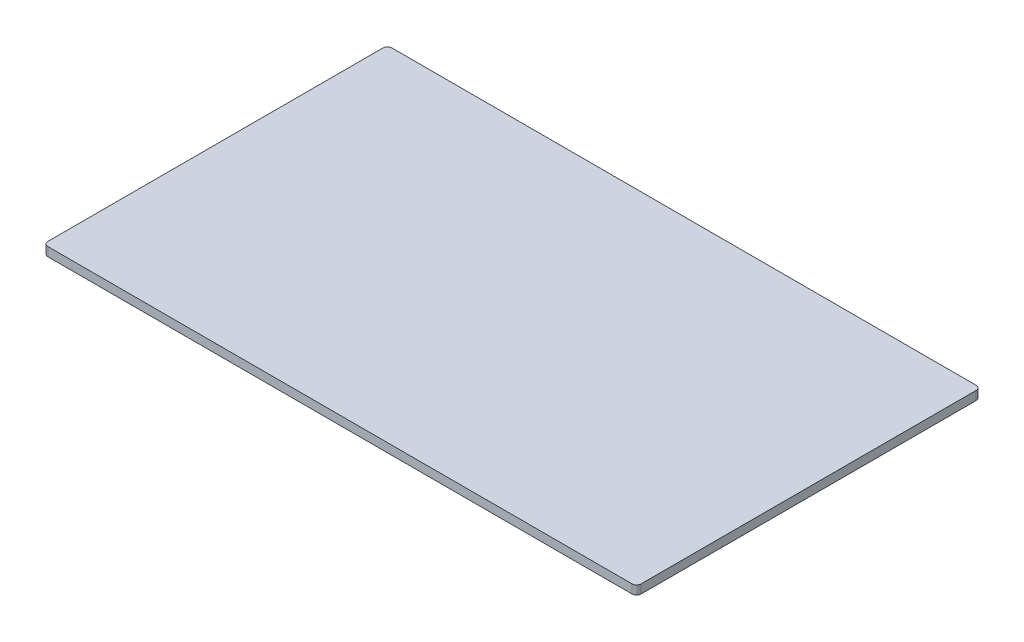
SolidWorks part; units mm, degrees
ref_plane "Front Plane" through (0, 0, 0) normal (0, 0, 1) x (1, 0, 0)
ref_plane "Top Plane" through (0, 0, 0) normal (0, 1, 0) x (1, 0, 0)
ref_plane "Right Plane" through (0, 0, 0) normal (1, 0, 0) x (0, 0, -1)
sketch "Sketch1" plane through (0, 0, 0) normal (0, 1, 0) x (1, 0, 0)
  line L1 (0, 0) -> (67.25, 0)
  line L2 (0, 0) -> (0, 39)
  line L3 (0, 39) -> (67.25, 39)
  line L4 (67.25, 0) -> (67.25, 39)
  dimension "D1" = 39
  dimension "D2" = 67.25
extrude "Boss-Extrude1" add sketch "Sketch1" along normal blind 1
fillet "Fillet1" radius 0.5 4 edges at (0, 0.5, -39) (67.25, 0.5, -39) (67.25, 0.5, 0) (0, 0.5, 0)
